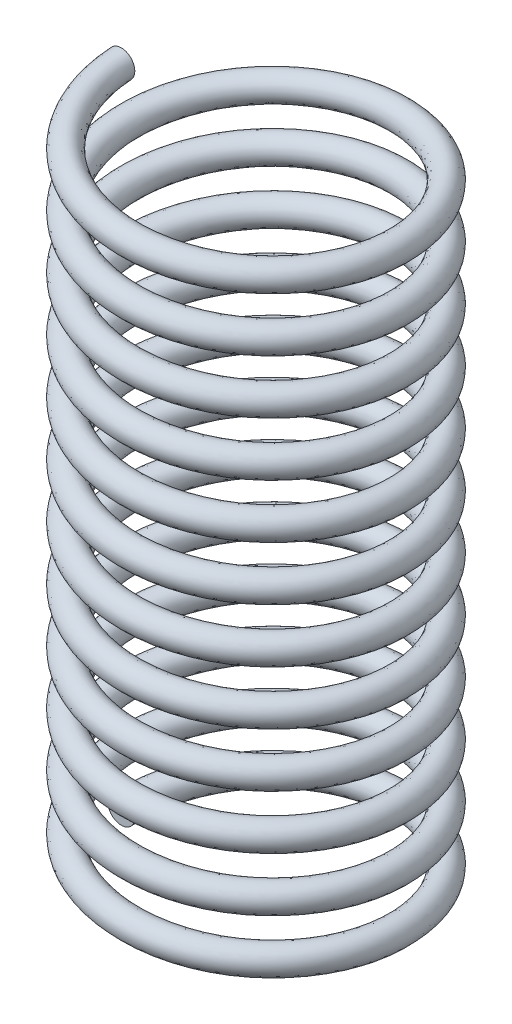
SolidWorks part; units mm, degrees
ref_plane "前视基准面" through (0, 0, 0) normal (0, 0, 1) x (1, 0, 0)
ref_plane "上视基准面" through (0, 0, 0) normal (0, 1, 0) x (1, 0, 0)
ref_plane "右视基准面" through (0, 0, 0) normal (1, 0, 0) x (0, 0, -1)
other "Configuration Table"
sketch "Sketch2" plane through (0, 0, 0) normal (0, 1, 0) x (1, 0, 0)
  circle A0 centre (0, 0) radius 2.5
sketch "Sketch4" plane through (0, 0, 0) normal (1, 0, 0) x (0, 0, -1)
  line L0 (0, 11.2933) -> (0, -0.4608)
curve "Helix/Spiral2" pitch 1 height 12 turns 12
sketch "Sketch6" plane through (0, 0, 0) normal (0, 0, 1) x (1, 0, 0)
  circle A0 centre (-2.5, 12) radius 0.25
  spline S0 degree 3 poles (-2.5, 0) (-2.5, 0.0207) (-2.3698, 0.0626) (-1.8138, 0.125) (-0.9816, 0.1875) (0, 0.25) (0.9816, 0.3125) (1.8138, 0.375) (2.3698, 0.4375) (2.5651, 0.5) (2.3698, 0.5625) (1.8138, 0.625) (0.7042, 0.7083) (-0.7042, 0.7917) (-1.8138, 0.875) (-2.3698, 0.9375) (-2.5651, 1) (-2.3698, 1.0625) (-1.8138, 1.125) (-0.7042, 1.2083) (0.7042, 1.2917) (1.8138, 1.375) (2.3698, 1.4375) (2.5651, 1.5) (2.3698, 1.5625) (1.8138, 1.625) (0.7042, 1.7083) (-0.7042, 1.7917) (-1.8138, 1.875) (-2.3698, 1.9375) (-2.5651, 2) (-2.3698, 2.0625) (-1.8138, 2.125) (-0.7042, 2.2083) (0.7042, 2.2917) (1.8138, 2.375) (2.3698, 2.4375) (2.5651, 2.5) (2.3698, 2.5625) (1.8138, 2.625) (0.7042, 2.7083) (-0.7042, 2.7917) (-1.8138, 2.875) (-2.3698, 2.9375) (-2.5651, 3) (-2.3698, 3.0625) (-1.8138, 3.125) (-0.7042, 3.2083) (0.7042, 3.2917) (1.8138, 3.375) (2.3698, 3.4375) (2.5651, 3.5) (2.3698, 3.5625) (1.8138, 3.625) (0.7042, 3.7083) (-0.7042, 3.7917) (-1.8138, 3.875) (-2.3698, 3.9375) (-2.5651, 4) (-2.3698, 4.0625) (-1.8138, 4.125) (-0.7042, 4.2083) (0.7042, 4.2917) (1.8138, 4.375) (2.3698, 4.4375) (2.5651, 4.5) (2.3698, 4.5625) (1.8138, 4.625) (0.7042, 4.7083) (-0.7042, 4.7917) (-1.8138, 4.875) (-2.3698, 4.9375) (-2.5651, 5) (-2.3698, 5.0625) (-1.8138, 5.125) (-0.7042, 5.2083) (0.7042, 5.2917) (1.8138, 5.375) (2.3698, 5.4375) (2.5651, 5.5) (2.3698, 5.5625) (1.8138, 5.625) (0.7042, 5.7083) (-0.7042, 5.7917) (-1.8138, 5.875) (-2.3698, 5.9375) (-2.5651, 6) (-2.3698, 6.0625) (-1.8138, 6.125) (-0.7042, 6.2083) (0.7042, 6.2917) (1.8138, 6.375) (2.3698, 6.4375) (2.5651, 6.5) (2.3698, 6.5625) (1.8138, 6.625) (0.7042, 6.7083) (-0.7042, 6.7917) (-1.8138, 6.875) (-2.3698, 6.9375) (-2.5651, 7) (-2.3698, 7.0625) (-1.8138, 7.125) (-0.7042, 7.2083) (0.7042, 7.2917) (1.8138, 7.375) (2.3698, 7.4375) (2.5651, 7.5) (2.3698, 7.5625) (1.8138, 7.625) (0.7042, 7.7083) (-0.7042, 7.7917) (-1.8138, 7.875) (-2.3698, 7.9375) (-2.5651, 8) (-2.3698, 8.0625) (-1.8138, 8.125) (-0.7042, 8.2083) (0.7042, 8.2917) (1.8138, 8.375) (2.3698, 8.4375) (2.5651, 8.5) (2.3698, 8.5625) (1.8138, 8.625) (0.7042, 8.7083) (-0.7042, 8.7917) (-1.8138, 8.875) (-2.3698, 8.9375) (-2.5651, 9) (-2.3698, 9.0625) (-1.8138, 9.125) (-0.7042, 9.2083) (0.7042, 9.2917) (1.8138, 9.375) (2.3698, 9.4375) (2.5651, 9.5) (2.3698, 9.5625) (1.8138, 9.625) (0.7042, 9.7083) (-0.7042, 9.7917) (-1.8138, 9.875) (-2.3698, 9.9375) (-2.5651, 10) (-2.3698, 10.0625) (-1.8138, 10.125) (-0.7042, 10.2083) (0.7042, 10.2917) (1.8138, 10.375) (2.3698, 10.4375) (2.5651, 10.5) (2.3698, 10.5625) (1.8138, 10.625) (0.7042, 10.7083) (-0.7042, 10.7917) (-1.8138, 10.875) (-2.3698, 10.9375) (-2.5651, 11) (-2.3698, 11.0625) (-1.8138, 11.125) (-0.7042, 11.2083) (0.7042, 11.2917) (1.8138, 11.375) (2.3698, 11.4375) (2.5651, 11.5) (2.3698, 11.5625) (1.8138, 11.625) (0.9816, 11.6875) (0, 11.75) (-0.9816, 11.8125) (-1.8138, 11.875) (-2.3698, 11.9374) (-2.5, 11.9793) (-2.5, 12) knots 0 0 0 0 0.005208 0.010417 0.015625 0.020833 0.026042 0.03125 0.036458 0.041667 0.046875 0.052083 0.057292 0.067708 0.072917 0.078125 0.083333 0.088542 0.09375 0.098958 0.109375 0.114583 0.119792 0.125 0.130208 0.135417 0.140625 0.151042 0.15625 0.161458 0.166667 0.171875 0.177083 0.182292 0.192708 0.197917 0.203125 0.208333 0.213542 0.21875 0.223958 0.234375 0.239583 0.244792 0.25 0.255208 0.260417 0.265625 0.276042 0.28125 0.286458 0.291667 0.296875 0.302083 0.307292 0.317708 0.322917 0.328125 0.333333 0.338542 0.34375 0.348958 0.359375 0.364583 0.369792 0.375 0.380208 0.385417 0.390625 0.401042 0.40625 0.411458 0.416667 0.421875 0.427083 0.432292 0.442708 0.447917 0.453125 0.458333 0.463542 0.46875 0.473958 0.484375 0.489583 0.494792 0.5 0.505208 0.510417 0.515625 0.526042 0.53125 0.536458 0.541667 0.546875 0.552083 0.557292 0.567708 0.572917 0.578125 0.583333 0.588542 0.59375 0.598958 0.609375 0.614583 0.619792 0.625 0.630208 0.635417 0.640625 0.651042 0.65625 0.661458 0.666667 0.671875 0.677083 0.682292 0.692708 0.697917 0.703125 0.708333 0.713542 0.71875 0.723958 0.734375 0.739583 0.744792 0.75 0.755208 0.760417 0.765625 0.776042 0.78125 0.786458 0.791667 0.796875 0.802083 0.807292 0.817708 0.822917 0.828125 0.833333 0.838542 0.84375 0.848958 0.859375 0.864583 0.869792 0.875 0.880208 0.885417 0.890625 0.901042 0.90625 0.911458 0.916667 0.921875 0.927083 0.932292 0.942708 0.947917 0.953125 0.958333 0.963542 0.96875 0.973958 0.979167 0.984375 0.989583 0.994792 1 1 1 1 construction
sweep "Sweep1" add profiles "Sketch6" path "Helix/Spiral2"
